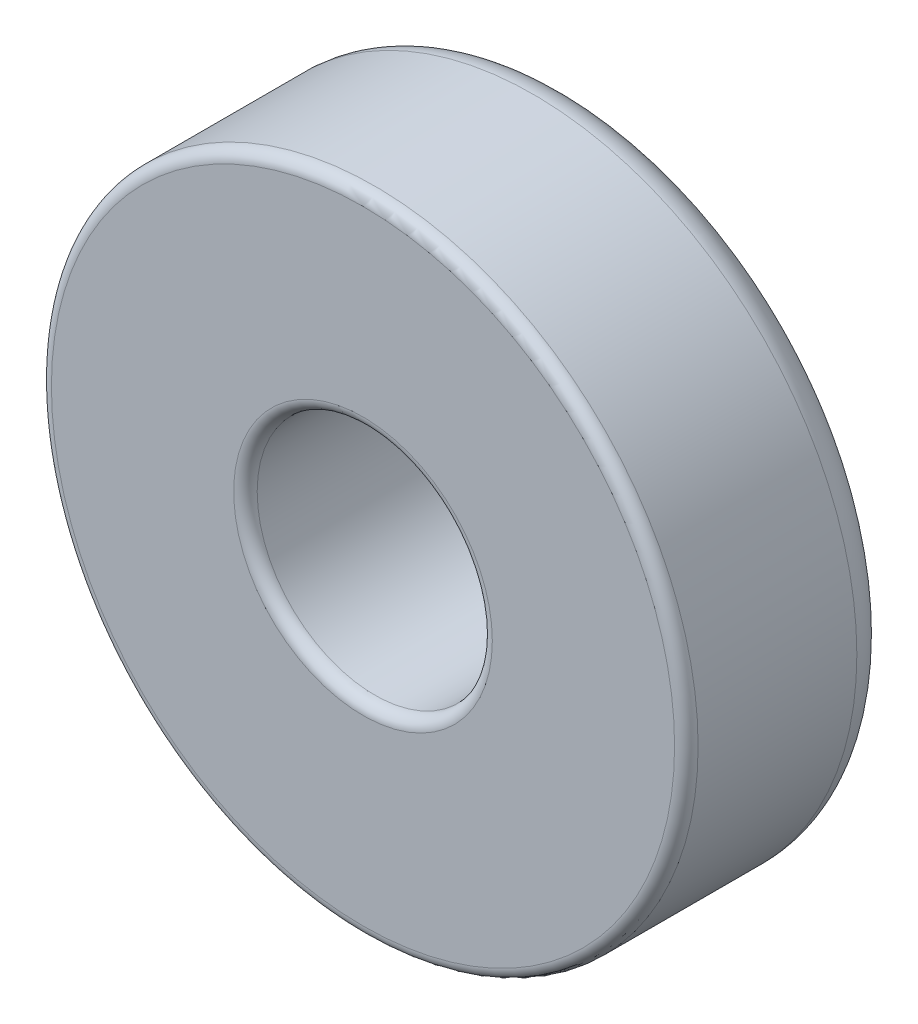
SolidWorks part; units mm, degrees
ref_plane "前视基准面" through (0, 0, 0) normal (0, 0, 1) x (1, 0, 0)
ref_plane "上视基准面" through (0, 0, 0) normal (0, 1, 0) x (1, 0, 0)
ref_plane "右视基准面" through (0, 0, 0) normal (1, 0, 0) x (0, 0, -1)
sketch "草图1" plane through (0, 0, 0) normal (0, 0, 1) x (1, 0, 0)
  circle A0 centre (0, 0) radius 1
  dimension "D1" = 2
extrude "拉伸-薄壁1" add sketch "草图1" along normal blind 1.75 thin
fillet "圆角1" radius 0.3 1 edges at (2.75, 0, 0)
fillet "圆角2" radius 0.1 3 edges at (1, 0, 0) (1, 0, 1.75) (2.75, 0, 1.75)
